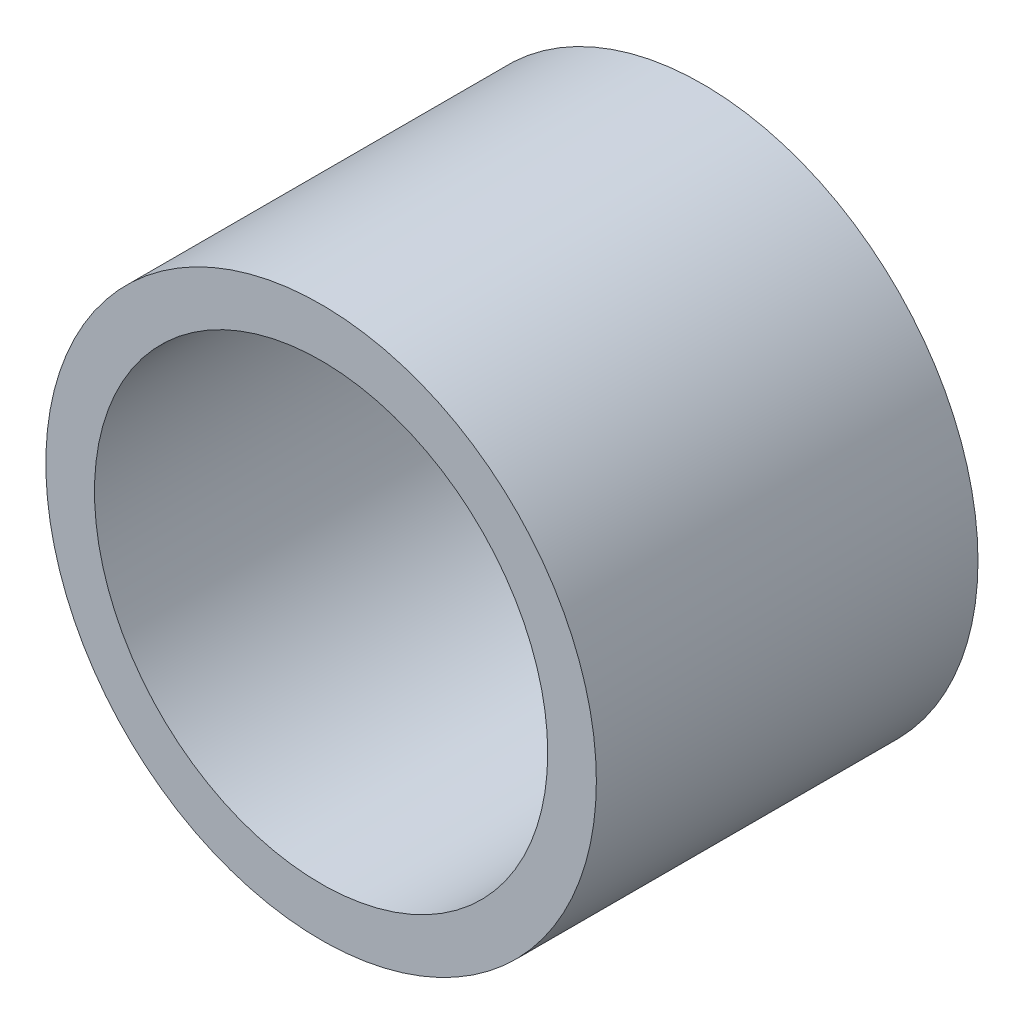
SolidWorks part; units mm, degrees
ref_plane "Front Plane" through (0, 0, 0) normal (0, 0, 1) x (1, 0, 0)
ref_plane "Top Plane" through (0, 0, 0) normal (0, 1, 0) x (1, 0, 0)
ref_plane "Right Plane" through (0, 0, 0) normal (1, 0, 0) x (0, 0, -1)
sketch "Sketch1" plane through (0, 0, 0) normal (0, 0, 1) x (1, 0, 0)
  circle A0 centre (0, 0) radius 15.8115
  dimension "D1" = 31.623
extrude "Boss-Extrude1" add sketch "Sketch1" along normal blind 21.9202
sketch "Sketch2" plane through (0, 0, 21.9202) normal (0, 0, 1) x (1, 0, 0)
  circle A3 centre (0, 0) radius 13.0175
  circle A4 centre (0, 0) radius 13.0175
  dimension "D1" = 2.794
extrude "Cut-Extrude1" cut sketch "Sketch2" against normal blind 19.3294
fillet "Fillet1" radius 0.3175 1 edges at (13.0175, 0, 2.5908)
